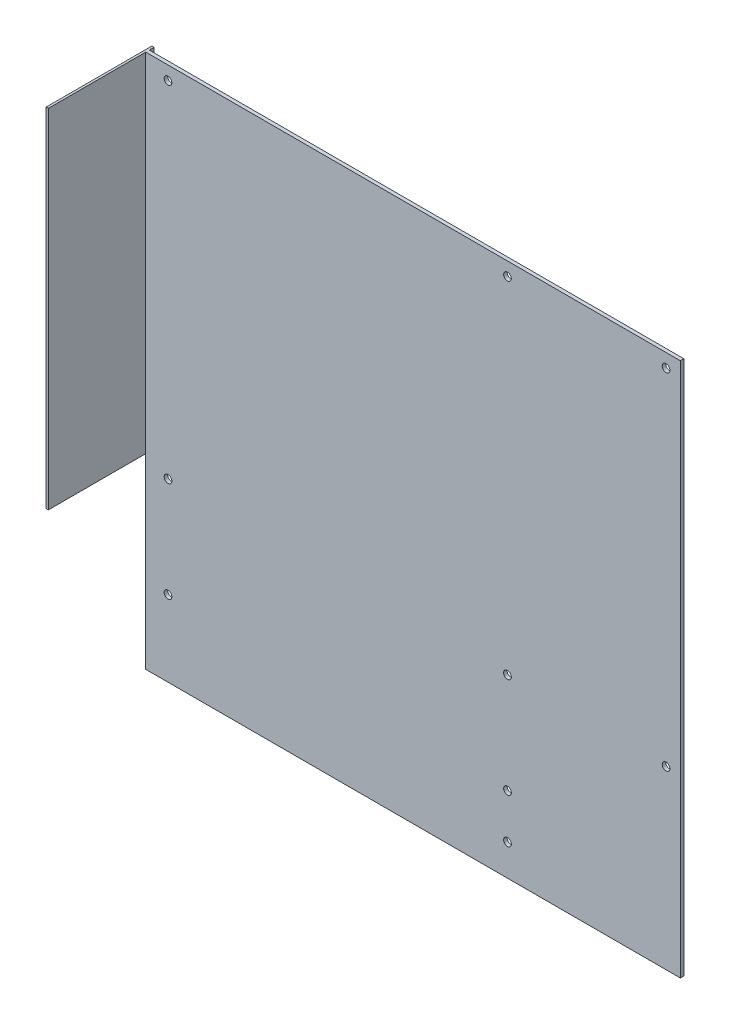
SolidWorks part; units mm, degrees
ref_plane "前视基准面" through (0, 0, 0) normal (0, 0, 1) x (1, 0, 0)
ref_plane "上视基准面" through (0, 0, 0) normal (0, 1, 0) x (1, 0, 0)
ref_plane "右视基准面" through (0, 0, 0) normal (1, 0, 0) x (0, 0, -1)
other "Configuration Table"
sketch "草图1" plane through (0, 0, 0) normal (0, 0, 1) x (1, 0, 0)
  line L0 (0, 0) -> (244, 0)
  line L1 (244, 0) -> (244, 244)
  line L2 (244, 244) -> (0, 244)
  line L3 (0, 244) -> (0, 0)
  dimension "D1" = 244
  dimension "D2" = 244
extrude "凸台-拉伸1" add sketch "草图1" along normal blind 1.6
sketch "草图2" plane through (0, 0, 1.6) normal (0, 0, 1) x (1, 0, 0)
  line L0 (0, 0) -> (244, 0) construction
  line L1 (0, 244) -> (0, 0) construction
  circle A0 centre (10.16, 34.63) radius 1.75
  circle A1 centre (10.16, 80.35) radius 1.75
  circle A2 centre (165.1, 34.63) radius 1.75
  circle A3 centre (165.1, 80.35) radius 1.75
  circle A4 centre (165.1, 14.31) radius 1.75
  circle A5 centre (237.49, 80.35) radius 1.75
  circle A6 centre (10.16, 237.83) radius 1.75
  circle A7 centre (165.1, 237.83) radius 1.75
  circle A8 centre (237.49, 237.83) radius 1.75
  point P6 (29.0389, 10.5336)
  point P9 (10.16, 40.3774)
  point P10 (10.16, 77.2544)
  point P11 (0, 0)
  point P16 (22.0056, 80.35)
  point P17 (22.1957, 34.63)
  point P18 (0, 0)
  point P19 (0, 0)
  point P20 (0, 0)
  point P21 (0, 0)
  point P22 (0, 0)
  point P23 (0, 0)
  point P26 (165.1, 14.1453)
  point P27 (0, 0)
  point P30 (216.2752, 80.35)
  point P31 (0, 0)
  point P32 (0, 0)
  point P39 (10.16, 106.3458)
  point P40 (165.1, 102.0354)
  point P41 (237.49, 101.8503)
  point P42 (0, 0)
  point P43 (0, 0)
  point P44 (0, 0)
  dimension "D1" = 3.5
  dimension "D4" = 3.5
  dimension "D6" = 3.5
  dimension "D7" = 3.5
  dimension "D9" = 3.5
  dimension "D12" = 3.5
  dimension "D13" = 3.5
  dimension "D14" = 3.5
  dimension "D15" = 3.5
  dimension "D2" = 34.63
  dimension "D3" = 10.16
  dimension "D5" = 45.72
  dimension "D8" = 154.94
  dimension "D10" = 14.31
  dimension "D11" = 72.39
  dimension "D16" = 157.48
extrude "切除-拉伸1" cut sketch "草图2" against normal through all contours A0 | A4 | A2 | A1 | A3 | A5 | A6 | A8 | A7
sketch "草图3" plane through (0, 0, 1.6) normal (0, 0, 1) x (1, 0, 0)
  line L0 (0, 244) -> (-1, 244)
  line L1 (-1, 244) -> (-1, 85.25)
  line L2 (-1, 85.25) -> (0, 85.25)
  line L3 (0, 244) -> (0, 0) construction
  line L8 (0, 244) -> (0, 0)
  line L9 (0, 0) -> (244, 0)
  line L10 (244, 0) -> (244, 244)
  line L11 (244, 244) -> (0, 244)
  line L12 (0, 244) -> (0, 85.25)
  dimension "D1" = 1
  dimension "D2" = 158.75
  dimension "D3" = 0
extrude "凸台-拉伸2" add sketch "草图3" along normal blind 44.45 and the other way blind 3.81
